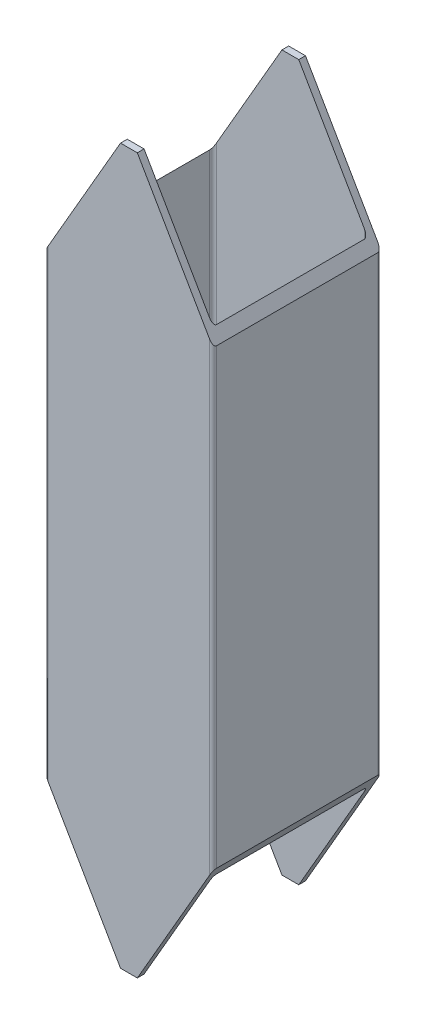
SolidWorks part; units mm, degrees
ref_plane "Plan de face" through (0, 0, 0) normal (0, 0, 1) x (1, 0, 0)
ref_plane "Plan de dessus" through (0, 0, 0) normal (0, 1, 0) x (1, 0, 0)
ref_plane "Plan de droite" through (0, 0, 0) normal (1, 0, 0) x (0, 0, -1)
sketch "Esquisse2" plane through (0, 0, 0) normal (0, 1, 0) x (1, 0, 0)
  line L0 (6, 96) -> (94, 96)
  line L1 (2, 0) -> (98, 0)
  line L2 (0, 2) -> (0, 98)
  line L3 (2, 100) -> (98, 100)
  line L4 (100, 2) -> (100, 98)
  line L5 (96, 6) -> (96, 94)
  line L6 (6, 4) -> (94, 4)
  line L7 (4, 6) -> (4, 94)
  line L8 (4, 4) -> (4, 96) construction
  line L9 (4, 96) -> (96, 96) construction
  line L10 (96, 4) -> (96, 96) construction
  line L11 (4, 4) -> (96, 4) construction
  line L12 (0, 0) -> (0, 100) construction
  line L13 (0, 0) -> (100, 0) construction
  line L14 (100, 0) -> (100, 100) construction
  line L15 (0, 100) -> (100, 100) construction
  arc A0 (4, 94) -> (6, 96) centre (6, 94) cw
  arc A1 (96, 6) -> (94, 4) centre (94, 6) cw
  arc A2 (6, 4) -> (4, 6) centre (6, 6) cw
  arc A3 (0, 2) -> (2, 0) centre (2, 2) ccw
  arc A4 (98, 0) -> (100, 2) centre (98, 2) ccw
  arc A5 (96, 94) -> (94, 96) centre (94, 94) ccw
  arc A6 (100, 98) -> (98, 100) centre (98, 98) ccw
  arc A7 (2, 100) -> (0, 98) centre (2, 98) ccw
  point P21 (0, 0)
  dimension "D4" = 2
  dimension "D1" = 100
  dimension "D2" = 100
  dimension "D3" = 4
extrude "Boss.-Extru.1" add sketch "Esquisse2" along normal blind 425
sketch "Esquisse3" plane through (0, 0, 0) normal (0, 0, 1) x (1, 0, 0)
  line L0 (50, 425) -> (45, 425) construction
  line L1 (2, 425) -> (98, 425) construction
  line L2 (45, 425) -> (0, 347.0577)
  line L3 (0, 425) -> (0, 0) construction
  line L4 (0, 347.0577) -> (-62.4502, 347.0577)
  line L5 (-62.4502, 347.0577) -> (-62.4502, 486.3017)
  line L6 (-62.4502, 486.3017) -> (45, 486.3017)
  line L7 (45, 486.3017) -> (45, 425)
  line L8 (45, 425) -> (0, 425) construction
  line L9 (0, 425) -> (0, 347.0577) construction
  line L10 (50, 0) -> (50, 425) construction
  line L11 (2, 0) -> (98, 0) construction
  line L12 (45, 425) -> (45, 0) construction
  line L13 (45, 0) -> (0, 77.9423)
  line L14 (0, 77.9423) -> (-44.1973, 77.9423)
  line L15 (-44.1973, 77.9423) -> (-44.1973, -11.8307)
  line L16 (-44.1973, -11.8307) -> (45, -11.8307)
  line L17 (45, -11.8307) -> (45, 0)
  line L18 (55, -11.8307) -> (55, 0)
  line L19 (144.1973, -11.8307) -> (55, -11.8307)
  line L20 (144.1973, 77.9423) -> (144.1973, -11.8307)
  line L21 (100, 77.9423) -> (144.1973, 77.9423)
  line L22 (55, 0) -> (100, 77.9423)
  line L23 (100, 425) -> (100, 347.0577) construction
  line L24 (55, 425) -> (100, 425) construction
  line L25 (55, 486.3017) -> (55, 425)
  line L26 (162.4502, 486.3017) -> (55, 486.3017)
  line L27 (162.4502, 347.0577) -> (162.4502, 486.3017)
  line L28 (100, 347.0577) -> (162.4502, 347.0577)
  line L29 (55, 425) -> (100, 347.0577)
  dimension "D1" = 5
  dimension "D2" = 60
  dimension "D3" = 60
extrude "Enlèv. mat.-Extru.1" cut sketch "Esquisse3" against normal through all
